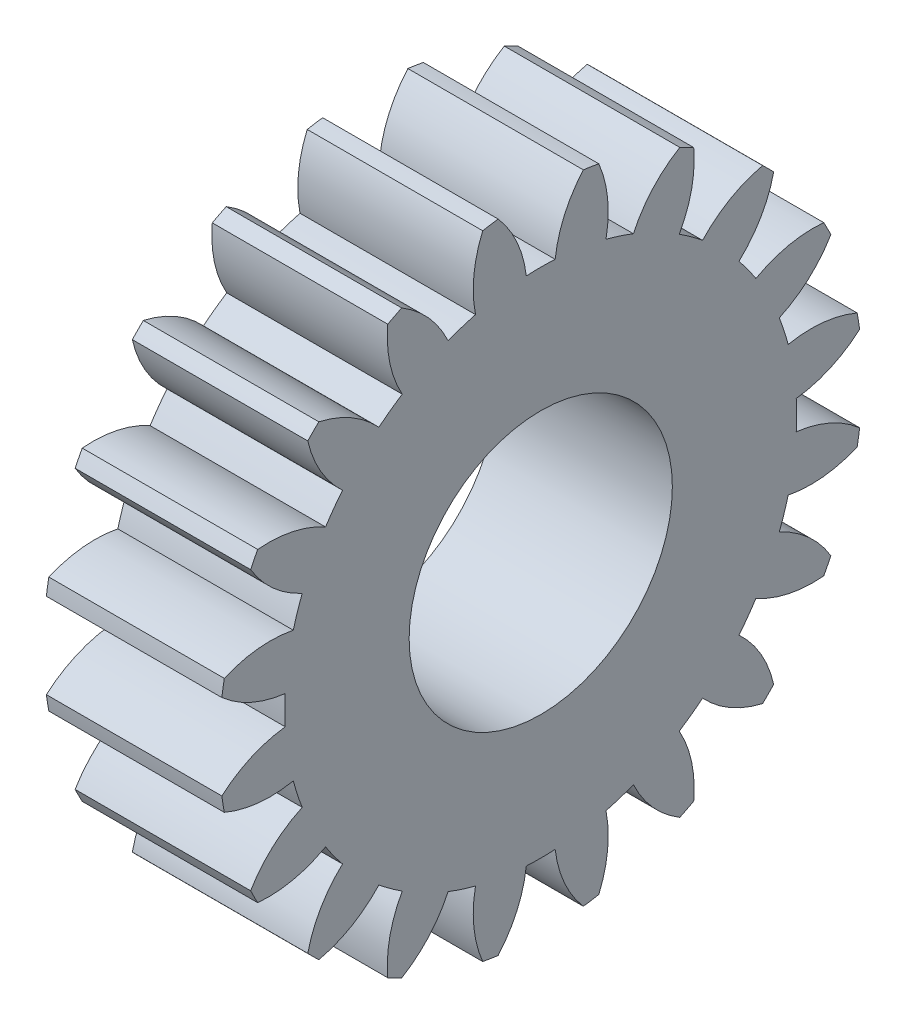
SolidWorks part; units mm, degrees
ref_plane "Plane1" through (0, 0, 0) normal (0, 0, 1) x (1, 0, 0)
ref_plane "Plane2" through (0, 0, 0) normal (0, 1, 0) x (1, 0, 0)
ref_plane "Plane3" through (0, 0, 0) normal (1, 0, 0) x (0, 0, -1)
sketch "HoldingSke" plane through (0, 0, 0) normal (0, 1, 0) x (1, 0, 0)
  line L0 (0, 0) -> (0.4698, -0.171)
  line L1 (-15, 0) -> (100, 0) construction
  line L2 (0, 0) -> (-2.1039, 2.3779)
  line L3 (0, 0) -> (-11.863, 4.5341)
  line L4 (0, 0) -> (8.1152, 2.9537)
  line L5 (0, 0) -> (-46.8476, -17.4728)
  line L6 (0, 0) -> (-9.9476, -6.7116)
  line L7 (-2.1039, 2.3779) -> (8.6586, 51.2059)
  line L8 (-76.2, 54.61) -> (-73.4, 54.61)
  line L9 (-71.009, 38.7566) -> (-53.1078, 45.2721)
  line L10 (-76.2, 71.12) -> (104.1128, 71.12)
  line L11 (0, 0) -> (-12, 0)
  line L12 (-76.2, 101.6) -> (-76.133, 101.6)
  line L13 (24.9733, 27.94) -> (52.9518, 28.4284)
  line L14 (24.9733, 27.94) -> (24.9743, 27.94)
  line L15 (24.9733, 27.94) -> (100.4006, 29.5858)
  line L16 (-63.627, -2) -> (-12.827, -2)
  circle A0 centre (0, 0) radius 9
  circle A1 centre (0, 0) radius 17.499
  circle A2 centre (0, 0) radius 37.5
  circle A3 centre (0, 0) radius 9
  dimension "MHD" = 34.998
  dimension "Hub_dia" = 75
  dimension "Bore" = 18
  dimension "MBD" = 18
  dimension "Num_teeth" = 20
  dimension "Pitch" = 0.5
  dimension "Overall_len" = 50
  dimension "Show_teeth" = 20
  dimension "Thickness" = 12
  dimension "OAL" = 50.0001
  dimension "T_dim" = 2.8
  dimension "Ap" = 20
  dimension "H" = 19.05
  dimension "Pitch_radius" = 180.3128
  dimension "Width" = 12
  dimension "Backlash" = 0.067
  dimension "Addendum_fac" = 1
  dimension "Dedendum_fac" = 1.25
  dimension "Clearance_fac" = 0.25
  dimension "Dedendum_add" = 0.001
  dimension "Module" = 2
sketch "BasProSke" plane through (0, 0, 0) normal (0, 1, 0) x (1, 0, 0)
  line L0 (-10, 0) -> (60, 0) construction
  line L1 (0, 0) -> (0, 22)
  line L2 (0, 0) -> (12, 0)
  line L3 (12, 0) -> (12, 22)
  line L4 (12, 22) -> (0, 22)
  dimension "Thickness" = 12
  dimension "Diameter" = 44
revolve "Base-Revolve" add sketch "BasProSke" angle 360 about L0
sketch "TooCutSke" plane through (0, 0, 0) normal (1, 0, 0) x (0, 0, -1)
  line L1 (0, 0) -> (0, 107) construction
  line L2 (0, 0) -> (-1.6864, 19.9288) construction
  line L3 (0, 0) -> (-6.2409, 39.4033) construction
  line L4 (-1.6864, 19.9288) -> (-3.1204, 19.7016) construction
  arc A0 (0.9862, 17.4712) -> (-0.9862, 17.4712) centre (0, 0) ccw
  arc A1 (2.9329, 21.8293) -> (-2.9329, 21.8293) centre (0, 0) ccw
  circle A2 centre (0, 0) radius 20 construction
  circle A3 centre (0, 0) radius 18.7939 construction
  arc A4 (-0.9862, 17.4712) -> (-2.9329, 21.8293) centre (-8.9313, 16.536) ccw
  arc A5 (2.9329, 21.8293) -> (0.9862, 17.4712) centre (8.9313, 16.536) ccw
  dimension "Root_dia" = 34.998
  dimension "Overcut_dia" = 44.0508
  dimension "Pitch_dia" = 40
  dimension "Base_dia" = 37.5877
  dimension "Flank_rad" = 8
  dimension "Half_ang" = 9
  dimension "Half_CT" = 1.4519
extrude "ToothCut" cut sketch "TooCutSke" along normal through all
fillet "Breaks" [suppressed] radius 0.04
fillet "RootFillets" [suppressed] radius 0.501
pattern_circular "TeethCuts" count 20 every 18 about axis through (-10, 0, 0) along (1, 0, 0) of "ToothCut", "RootFillets", "Breaks"
sketch "HubNeaOneSke" plane through (0, 0, 0) normal (-1, 0, 0) x (0, 0, 1)
  circle A0 centre (0, 0) radius 17.499
  dimension "Diameter" = 34.998
extrude "HubNearOne" [suppressed] add sketch "HubNeaOneSke" along normal blind 38.0001
sketch "HubNeaBotSke" plane through (0, 0, 0) normal (-1, 0, 0) x (0, 0, 1)
  circle A0 centre (0, 0) radius 17.499
  dimension "Diameter" = 34.998
extrude "HubNearBoth" [suppressed] add sketch "HubNeaBotSke" along normal blind 19
ref_plane "FarPln" through (12, 0, 0) normal (1, 0, 0) x (0, 0, -1)
sketch "HubFarSke" plane through (12, 0, 0) normal (1, 0, 0) x (0, 0, -1)
  circle A0 centre (0, 0) radius 17.499
  dimension "Diameter" = 34.998
extrude "HubFar" [suppressed] add sketch "HubFarSke" along normal blind 19
sketch "BorSke" plane through (0, 0, 0) normal (1, 0, 0) x (0, 0, -1)
  circle A0 centre (0, 0) radius 9
  dimension "Diameter" = 18
extrude "Bore" cut sketch "BorSke" along normal mid plane 100.0001
sketch "KeySke" plane through (0, 0, 0) normal (1, 0, 0) x (0, 0, -1)
  line L0 (-3, 0) -> (-3, 11.8)
  line L1 (-3, 11.8) -> (3, 11.8)
  line L2 (3, 11.8) -> (3, 0)
  line L3 (0, 0) -> (0, 34) construction
  line L4 (-3, 0) -> (3, 0)
  dimension "Offset" = 11.8
  dimension "Width" = 6
extrude "Keyway" [suppressed] cut sketch "KeySke" along normal mid plane 100.0001
pattern_circular "Keyway2" [suppressed] count 2 every 90 about axis through (-10, 0, 0) along (1, 0, 0)
equation "' \"Module@HoldingSke\" = 6.35"
equation "' \"Num_teeth@HoldingSke\" = 12"
equation "' \"Ap@HoldingSke\" =  20"
equation "' \"Ap@HoldingSke\" = 20"
equation "' \"Width@HoldingSke\" = 0.5 * 25.4"
equation "' \"Hub_dia@HoldingSke\"= 1 * 25.4"
equation "' \"Hub_dia@HoldingSke\" = 1 * 25.4"
equation "' \"Overall_len@HoldingSke\" = 1.0 * 25.4"
equation "' \"Bore@HoldingSke\" = 0.75 * 25.4"
equation "' \"T_dim@HoldingSke\" = 0.1 * 25.4"
equation "' \"Width@KeySke\" = 0.25 * 25.4"
equation "' \"Show_teeth@HoldingSke\" = 13"
equation "' \"Backlash@HoldingSke\" = 0.009 * 25.4"
equation "' \"Addendum_fac@HoldingSke\" = 1.0"
equation "' \"Dedendum_fac@HoldingSke\" = 1.25"
equation "' \"Dedendum_add@HoldingSke\" = 0.00005 * 25.4"
equation "' \"Clearance_fac@HoldingSke\" = 0.25"
equation "\"Pitch@HoldingSke\" = 1 / \"Module@HoldingSke\""
equation "\"Overcut_dia@TooCutSke\" = (\"Num_teeth@HoldingSke\" + 2 * \"Addendum_fac@HoldingSke\") / \"Pitch@HoldingSke\" + 0.002 * 25.4"
equation "\"Pitch_dia@TooCutSke\" = \"Num_teeth@HoldingSke\" / \"Pitch@HoldingSke\""
equation "\"Base_dia@TooCutSke\" = \"Num_teeth@HoldingSke\" / \"Pitch@HoldingSke\" * cos((\"Ap@HoldingSke\"  * 3.14159265 / 180))"
equation "\"Root_dia@TooCutSke\" = (\"Num_teeth@HoldingSke\" + 2) / \"Pitch@HoldingSke\" - 2 * (\"Addendum_fac@HoldingSke\" + \"Dedendum_fac@HoldingSke\") / \"Pitch@HoldingSke\" - \"Dedendum_add@HoldingSke\" * 2"
equation "\"Half_ang@TooCutSke\" = 180 / \"Num_teeth@HoldingSke\""
equation "\"Half_CT@TooCutSke\" = \"Num_teeth@HoldingSke\" / \"Pitch@HoldingSke\" * sin((3.14159265 / 2 / \"Num_teeth@HoldingSke\")) / 2 - 7 * \"Backlash@HoldingSke\" / 4"
equation "\"Flank_rad@TooCutSke\" = \"Num_teeth@HoldingSke\" / \"Pitch@HoldingSke\" / 5"
equation "\"Radius@RootFillets\" = \"Clearance_fac@HoldingSke\" / \"Pitch@HoldingSke\" + \"Dedendum_add@HoldingSke\""
equation "\"Break_rad@Breaks\" = 0.02 / \"Pitch@HoldingSke\""
equation "\"Thickness@HoldingSke\" = \"Width@HoldingSke\""
equation "\"OAL@HoldingSke\" = \"Thickness@HoldingSke\""
equation "\"MHD@HoldingSke\" = (\"Num_teeth@HoldingSke\" + 2) / \"Pitch@HoldingSke\" - 2 * (\"Addendum_fac@HoldingSke\" + \"Dedendum_fac@HoldingSke\")  / \"Pitch@HoldingSke\" - \"Dedendum_add@HoldingSke\" * 2"
equation "\"MBD@HoldingSke\" = (\"Num_teeth@HoldingSke\" + 2) / \"Pitch@HoldingSke\" - 2 * (\"Addendum_fac@HoldingSke\" + \"Dedendum_fac@HoldingSke\")  / \"Pitch@HoldingSke\" - \"Dedendum_add@HoldingSke\" * 2 - 0.002 * 25.4"
equation "\"MHD@HoldingSke\" = ((sgn( \"MHD@HoldingSke\" - \"Hub_dia@HoldingSke\" )-1)*( \"MHD@HoldingSke\" - \"Hub_dia@HoldingSke\" ))/-2+ \"Hub_dia@HoldingSke\""
equation "\"MBD@HoldingSke\" = ((sgn( \"MBD@HoldingSke\" - \"Bore@HoldingSke\" )-1)*( \"MBD@HoldingSke\" - \"Bore@HoldingSke\" ))/-2+ \"Bore@HoldingSke\""
equation "\"OAL@HoldingSke\" = ((sgn( \"OAL@HoldingSke\" - \"Overall_len@HoldingSke\" )+1)*( \"OAL@HoldingSke\" - \"Overall_len@HoldingSke\" ))/2 + \"Overall_len@HoldingSke\" + 0.000002 * 25.4"
equation "\"Num_teeth@TeethCuts\" = int( \"Show_teeth@HoldingSke\" ) + 1"
equation "\"Num_teeth@TeethCuts\" = ((sgn( \"Num_teeth@TeethCuts\" - \"Num_teeth@HoldingSke\" )-1)*( \"Num_teeth@TeethCuts\" - \"Num_teeth@HoldingSke\" ))/-2+ \"Num_teeth@HoldingSke\""
equation "\"Num_teeth@TeethCuts\" = ((sgn( \"Num_teeth@TeethCuts\" - 2.0)+1)*( \"Num_teeth@TeethCuts\" - 2.0))/2 +2.0"
equation "\"Angle@TeethCuts\" = 360.0 / \"Num_teeth@HoldingSke\""
equation "\"Diameter@BasProSke\" = (\"Num_teeth@HoldingSke\" + 2 * \"Addendum_fac@HoldingSke\") / \"Pitch@HoldingSke\""
equation "\"Thickness@BasProSke\"  = \"Thickness@HoldingSke\""
equation "' \"Fillet_rad@BasProSke\" =  \"Thickness@HoldingSke\" * 0.05"
equation "' \"Fillet_rad@BasProSke\" = \"Thickness@HoldingSke\" * 0.05"
equation "\"MHD@HoldingSke\" = ((sgn( \"MHD@HoldingSke\" - \"Root_dia@TooCutSke\" )-1)*( \"MHD@HoldingSke\" - \"Root_dia@TooCutSke\" ))/-2+ \"Root_dia@TooCutSke\""
equation "\"Diameter@HubNeaOneSke\" = \"MHD@HoldingSke\""
equation "\"Length@HubNearOne\" = \"OAL@HoldingSke\" - \"Thickness@BasProSke\""
equation "\"Diameter@HubNeaBotSke\" = \"MHD@HoldingSke\""
equation "\"Length@HubNearBoth\" = ( \"OAL@HoldingSke\" - \"Thickness@BasProSke\" ) / 2.0"
equation "\"Thickness@FarPln\" = \"Thickness@BasProSke\""
equation "\"Diameter@HubFarSke\" = \"MHD@HoldingSke\""
equation "\"Length@HubFar\" = ( \"OAL@HoldingSke\" - \"Thickness@BasProSke\" ) / 2.0"
equation "\"Diameter@BorSke\" = \"MBD@HoldingSke\""
equation "\"D1@Bore\" = \"OAL@HoldingSke\" * 2.0"
equation "\"D1@Keyway\" = \"OAL@HoldingSke\" * 2.0"
equation "\"Offset@KeySke\" = \"T_dim@HoldingSke\" + \"MBD@HoldingSke\" / 2.0"
